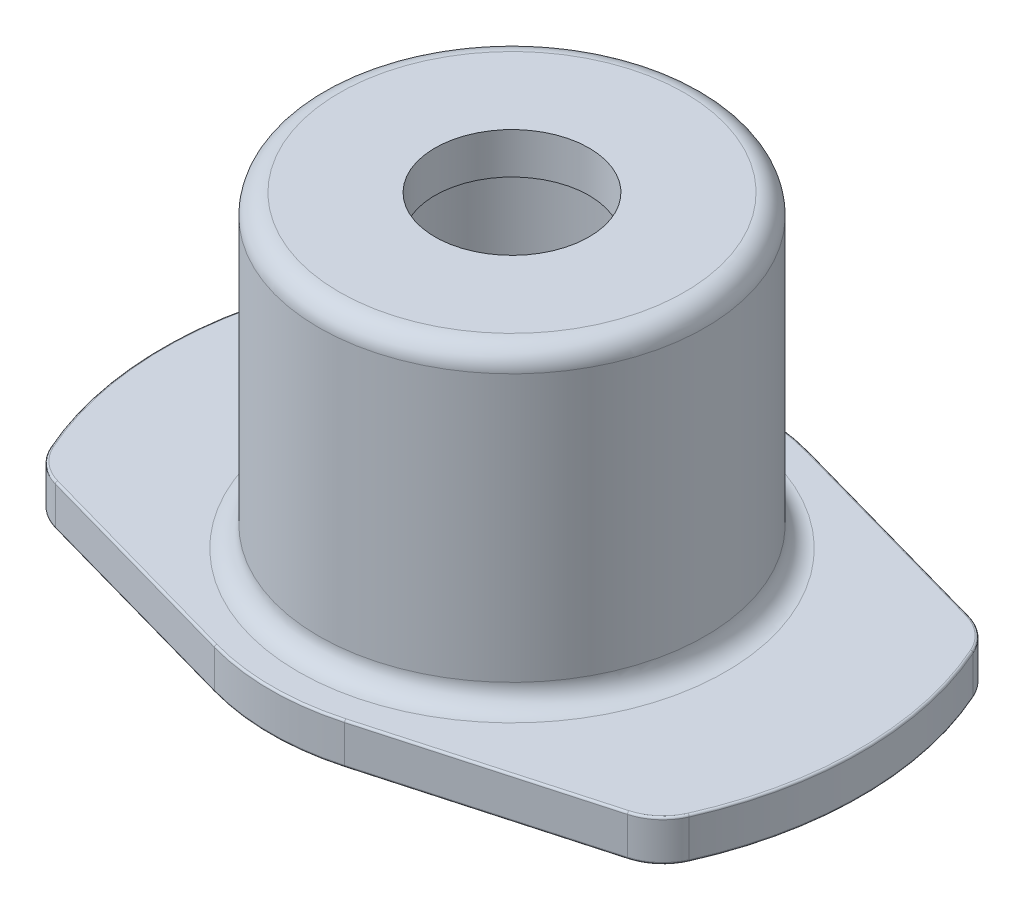
SolidWorks part; units mm, degrees
ref_plane "Front Plane" through (0, 0, 0) normal (0, 0, 1) x (1, 0, 0)
ref_plane "Top Plane" through (0, 0, 0) normal (0, 1, 0) x (1, 0, 0)
ref_plane "Right Plane" through (0, 0, 0) normal (1, 0, 0) x (0, 0, -1)
sketch "Sketch6" plane through (0, 0, 0) normal (0, 1, 0) x (1, 0, 0)
  line L0 (-3.1698, 11.3144) -> (-13.9222, 8.302)
  line L1 (3.1698, 11.3144) -> (13.9222, 8.302)
  line L2 (-3.1698, -11.3144) -> (-13.9222, -8.302)
  line L3 (3.1698, -11.3144) -> (13.9222, -8.302)
  line L4 (-15, -1001.3272) -> (-15, 48998.6728) construction
  line L5 (15, -1000.9789) -> (15, 48999.0211) construction
  arc A0 (-3.1698, -11.3144) -> (3.1698, -11.3144) centre (0, 0) ccw
  arc A1 (-15.5319, 6.911) -> (-15.5319, -6.911) centre (0, 0) ccw
  arc A2 (3.1698, 11.3144) -> (-3.1698, 11.3144) centre (0, 0) ccw
  arc A3 (15.5319, -6.911) -> (15.5319, 6.911) centre (0, 0) ccw
  arc A4 (13.9222, 8.302) -> (15.5319, 6.911) centre (13.2478, 5.8947) cw
  arc A5 (15.5319, -6.911) -> (13.9222, -8.302) centre (13.2478, -5.8947) cw
  arc A6 (-13.9222, -8.302) -> (-15.5319, -6.911) centre (-13.2478, -5.8947) cw
  arc A7 (-15.5319, 6.911) -> (-13.9222, 8.302) centre (-13.2478, 5.8947) cw
  point P15 (15, 8)
  point P19 (15, -8)
  point P22 (-15, -8)
  point P25 (-15, 8)
  dimension "D1" = 34
  dimension "D2" = 23.5
  dimension "D5" = 2.5
  dimension "D6" = 2.5
  dimension "D7" = 2.5
  dimension "D8" = 2.5
  dimension "D3" = 15
  dimension "D4" = 15
extrude "Boss-Extrude3" add sketch "Sketch6" along normal blind 2
sketch "Sketch2" plane through (0, 2, 0) normal (0, 1, 0) x (1, 0, 0)
  circle A0 centre (0, 0) radius 9.4
  dimension "D1" = 18.8
extrude "Boss-Extrude2" add sketch "Sketch2" along normal blind 15
sketch "Sketch3" plane through (0, 0, 0) normal (0, -1, 0) x (1, 0, 0)
  circle A0 centre (0, 0) radius 5.105
  dimension "D1" = 10.21
extrude "Cut-Extrude1" cut sketch "Sketch3" against normal blind 15
sketch "Sketch4" plane through (0, 15, 0) normal (0, -1, 0) x (1, 0, 0)
  circle A0 centre (0, 0) radius 3.75
  dimension "D1" = 7.5
extrude "Cut-Extrude2" cut sketch "Sketch4" against normal through all
fillet "Fillet2" radius 1 2 edges at (0, 17, 9.4) (0, 2, -9.4)
fillet "Fillet4" radius 0.1 24 edges at (-14.8824, 0, 7.7862) (-17, 0, 0) (-14.8824, 0, -7.7862) (-8.546, 0, -9.8082) (0, 0, -11.75) (8.546, 0, -9.8082) (14.8824, 0, -7.7862) (17, 0, 0) (14.8824, 0, 7.7862) (8.546, 0, 9.8082) (0, 0, 11.75) (-14.8824, 2, 7.7862) (-17, 2, 0) (-14.8824, 2, -7.7862) (-8.546, 2, -9.8082) (0, 2, -11.75) (8.546, 2, -9.8082) (14.8824, 2, -7.7862) (17, 2, 0) (14.8824, 2, 7.7862) (8.546, 2, 9.8082) (0, 2, 11.75) (-8.546, 0, 9.8082) (-8.546, 2, 9.8082)
equation "\"`7\"=19"
